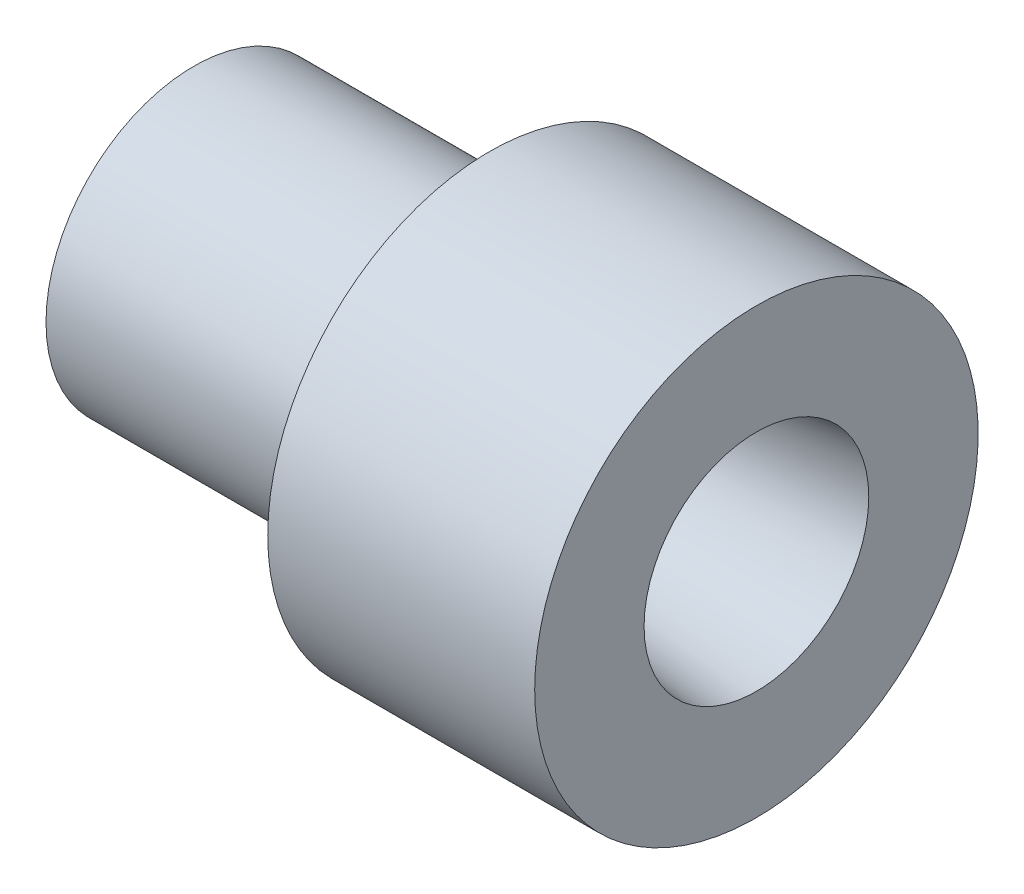
SolidWorks part; units mm, degrees
ref_plane "Front Plane" through (0, 0, 0) normal (0, 0, 1) x (1, 0, 0)
ref_plane "Top Plane" through (0, 0, 0) normal (0, 1, 0) x (1, 0, 0)
ref_plane "Right Plane" through (0, 0, 0) normal (1, 0, 0) x (0, 0, -1)
sketch "Sketch1" plane through (0, 0, 0) normal (0, 1, 0) x (1, 0, 0)
  line L0 (0, 0) -> (0, 2.286) construction
  line L1 (0, 2.286) -> (0, 6.35)
  line L2 (12.7, 9.525) -> (24.1665, 9.525)
  line L3 (24.1665, 9.525) -> (24.1665, 4.826)
  line L4 (24.1665, 4.826) -> (0, 2.286)
  line L5 (0, 0) -> (24.1665, 0) construction
  line L6 (24.1665, 0) -> (24.1665, 4.826) construction
  line L8 (12.7, 6.35) -> (12.7, 9.525)
  line L12 (0, 6.35) -> (12.7, 6.35)
  dimension "D1" = 2.286
  dimension "D2" = 4.826
  dimension "D3" = 6
  dimension "D4" = 9.525
  dimension "D5" = 6.35
  dimension "D6" = 12.7
revolve "Revolve1" add sketch "Sketch1" angle 360 about L5
equation "\"z\" = 8\t\t\t\t'number of blades"
equation "\"de\" = 0.43in\t\t\t'entrance eye diameter"
equation "\"de_length\" = 4mm\t\t'entrance eye consistent length"
equation "\"d_exit\" = 0.18in \t\t'throat aka d1"
equation "\"d2\" = 2.1in \t\t\t'outer diameter of the impeller"
equation "\"b2\" = .2in\t\t\t'tip height from disc surface at d2; slightly higher than d_exit"
equation "\"b1\" = \"b2\" + (\"d2\"/2 - \"de\"/2)*tan(\"theta\") \t\t\t'tip height from disc surface at inlet eye"
equation "\"theta\" = 12\t\t\t'angle of blades from inner to outer "
equation "\"ae\" = 3.14*(\"de\"^2)/4\t\t'entrance eye area'"
equation "\"ce\" = 3.14*\"de\"\t\t'entrance eye circumference"
equation "\"av_ratio\" = .325\t\t'ratio of av/ae at N_s of 470, range is .275 to .375, .325 ideal. High ratio means bigger area means smaller blades"
equation "\"av\" = \"ae\"*\"av_ratio\"\t\t'area between just two blades"
equation "\"s_open\" = \"av\"/\"b1\"\t\t'width of open area"
equation "\"s\"=\"ce\" - \"z\"*\"s_open\""
equation "\"min blade thickness\" = .15in"
equation "\"bearing OD\" = 30mm"
equation "\"bearing ID\"= 10mm"
equation "\"bearing depth\"= 9mm"
equation "\"bearing outer race thickness\"= 1mm"
equation "\"bearing inner race thickness\"= 1mm"
equation "\"bearing bore\" = \"bearing depth\" + 1mm"
equation "\"lower seal OD\" = .917in\t\t'this is https://www.mcmaster.com/#9281k121/=174001b"
equation "\"lower seal ID\"= .375in"
equation "\"lower seal depth\" = .625in + .218in"
equation "\"lower seal bore\" = \"lower seal depth\" + 1mm"
equation "\"upper seal OD\" = 1.125in\t'this is https://www.mcmaster.com/#5154t33/=173zuau, needs to be visually inspected before machining!"
equation "\"upper seal ID\"= 0.625in"
equation "\"upper seal depth\"= .25in\t'aka height; these values need to be confirmed by inspection!! We may want to compress the height."
equation "\"upper seal bore\" = \"upper seal depth\" + 1mm"
equation "\"big o-ring thickness\" = .139in"
equation "\"big o-ring OD\" = 2.734in"
equation "\"big o-ring ID\" = 3.012in"
equation "\"big o-ring groove depth\" = \"big o-ring thickness\"*4/5"
equation "\"impeller center height\" = \"impeller base thickness\" + \"b1\"\t'impeller height at de"
equation "\"impeller outer height\" = \"impeller base thickness\" + \"b2\"\t'impeller height at de"
equation "\"impeller upper clearance\"= .5mm"
equation "\"impeller horizontal clearance\"= (\"d2\"*1.15 - \"d2\")/2 \t\t'clearance based on D2-D3 ratio for circular volute, ranges 1.15 to 1.2"
equation "\"impeller bottom clearance\"= .5mm"
equation "\"impeller base thickness\"= 2mm"
equation "\"impeller dowel diameter\" = 2mm"
equation "\"impeller bolt head diameter\" = \"m4 head bore diameter\""
equation "\"impeller bolt head depth\" = 4mm"
equation "\"impeller bolt stop depth\" = 3mm"
equation "\"impeller bolt bore\" = \"m4 clearance\""
equation "\"impeller shaft bore depth\" = 12mm"
equation "\"impeller shaft bore\" = 8mm"
equation "\"impeller boss depth\" = \"impeller shaft bore depth\"+\"impeller bolt stop depth\"+\"impeller bolt head depth\"-\"impeller base thickness\""
equation "\"impeller boss diameter\" = \"upper seal ID\""
equation "\"impeller dowel length\" = 2mm*2 + \"impeller shaft bore\""
equation "\"coupler motor shaft hole ID\"= 8mm"
equation "\"coupler OD\"= 17mm"
equation "\"coupler length\"= 25mm"
equation "\"motor OD\" = 64mm"
equation "\"motor shaft diameter\"= 8mm"
equation "\"motor shaft pride\"= 32mm"
equation "\"motor to bearing plate distance\" = \"motor shaft pride\" + 2mm +\"coupler length\"/2"
equation "\"square plate bolt bore\" = \"m8 clearance\""
equation "\"square plate bolt head diameter\" = 13.5mm"
equation "\"square plate bolt head depth\" = 8mm"
equation "\"square plate bolt pattern diameter\"= 3.5in"
equation "\"motor mount center bore\"= \"coupler OD\"+ 4mm"
equation "\"motor mount post radius\"= ( 3 * \"square plate bolt bore\" ) / 2"
equation "\"motor mount m4 screw hole diameter\"= 4mm"
equation "\"motor mount m4 head diameter\"= 7.25mm"
equation "\"motor mount m4 head depth\"= 4mm"
equation "\"motor mount m4 pattern diamater\" = 30mm"
equation "\"motor mount plate thickness\"= 8mm + \"motor mount m4 head depth\""
equation "\"bearing plate stop ID\" = \"bearing OD\" - 4mm"
equation "\"bearing plate stop depth\" = 3mm"
equation "\"bearing plate thickness\" = \"bearing bore\" + \"bearing plate stop depth\" + \"shaft bearing stop length\""
equation "\"lower seal plate lip depth\" = 2mm"
equation "\"lower seal plate lip ID\" = \"lower seal OD\" - 3mm"
equation "\"lower seal plate thickness\" = \"lower seal plate lip depth\" + \"lower seal bore\""
equation "\"shaft coupler section diameter\" = 8mm"
equation "\"shaft coupler section length\" = \"motor to bearing plate distance\" - \"motor shaft pride\" - 2mm"
equation "\"shaft bearing section diameter\" = \"bearing ID\""
equation "\"shaft bearing section length\" = \"bearing plate stop depth\" + \"bearing depth\""
equation "\"shaft bearing stop diameter\" = \"bearing ID\" + 4mm"
equation "\"shaft bearing stop length\" = 3mm"
equation "\"shaft lower seal section diameter\" = \"lower seal ID\""
equation "\"shaft lower seal section length\" = \"lower seal plate thickness\" + 1mm"
equation "\"shaft impeller section diameter\" = \"impeller shaft bore\""
equation "\"shaft impeller section length\" = \"upper seal plate thickness\" + \"upper seal plate riser\" + \"impeller bottom clearance\" + \"impeller base thickness\" - \"impeller bolt head depth\" - \"impeller bolt stop depth\""
equation "\"upper seal plate thickness\" = \"upper seal plate pressure hole diameter\"+10mm"
equation "\"upper seal plate lip ID\" = \"upper seal OD\" - 3mm"
equation "\"upper seal plate riser\" = 6.59mm \t\t'this number needs to be read from the housing file"
equation "\"upper seal plate pressure hole diameter\" = .125in\t'this is 1/8 drill "
equation "\"upper seal plate pressure tap diameter\" = .328125in \t'this is 21/64 drill for a 1/8 ANPT tap"
equation "\"upper seal plate pressure tap grip\" = 5mm\t\t'this is the area around the tap so it doesn't crack"
equation "\"upper seal plate pressure tap depth\" = 12mm"
equation "\"impeller cavity center height\"= \"impeller bottom clearance\" + \"impeller upper clearance\" + \"impeller center height\""
equation "\"impeller cavity diameter\"= 2 * \"impeller horizontal clearance\" + \"d2\" \t\t\t\t\t\t\t\t\t'called D3 analytically"
equation "\"impeller cavity outer height\"= \"impeller bottom clearance\" + \"impeller upper clearance\" + \"impeller base thickness\" + \"b2\" \t\t'this is height at impeller diameter d2, not at d3"
equation "\"impeller housing thickness\"= \"impeller housing exit threaded diameter\" + 2*\"impeller housing outlet grip\""
equation "\"impeller housing diameter\" = \"square plate bolt pattern diameter\" + 2*\"motor mount post radius\""
equation "\"impeller housing bolt count\" = 8"
equation "\"impeller housing bolt diameter\" = \"m6 clearance\""
equation "\"impeller housing bolt pattern diameter\" = 3.5in"
equation "\"impeller housing threaded inlet diameter\" = 0.71875in \t'this is the 23/32 drill size for 1/2 NPT fitting https://www.mcmaster.com/#50715k269/=176pljy"
equation "\"impeller housing threaded inlet depth\"= .6in"
equation "\"impeller housing exit threaded diameter\"= 0.515625in \t\t'this is the 33/64 drill size for 9/16-18 fitting, expecting swagelok SS-8FK0-1-6STH fitting"
equation "\"impeller housing exit threaded depth\"= 10mm"
equation "\"impeller housing diffuser conical angle\"=10"
equation "\"impeller housing diffuser tangent angle\"=5"
equation "\"impeller housing diffuser final diameter\" = .38in\t\t'aka d2'"
equation "\"impeller housing outlet grip\" = 5mm"
equation "\"end mill size\" = 0.375in\t'for 3/8 endmill"
equation "\"m4 clearance\" = 0.171875in \t'this is 11/64 bit for 4.36mm"
equation "\"m4 tap\" = 0.125in\t\t'this is 1/8 bit for 3.17mm"
equation "\"m4 head bore diameter\" = 7.5mm"
equation "\"m4 head bore depth\" = 5mm\t'actual is ~4mm"
equation "\"m6 clearance\" = 0.234375in\t'this is 15/64 bit = 5.95mm, could use 6mm bit, B bit for 6.04mm or 1/4 bit for 6.35mm"
equation "\"m6 tap\" = 5mm\t\t\t'5mm is appropriate, could use 13/64 or #5,6,7"
equation "\"m6 head bore diameter\" = 11mm\t\t"
equation "\"m6 head bore depth\" = 7mm\t'actual is 6mm"
equation "\"m8 clearance\" = 0.3125in\t'this is 5/16in for 7.93mm, could use 8mm, O,P, or 21/64"
equation "\"m8 tap\" = 0.265625in\t\t'this is 17/64 for 6.746875mm"
equation "\"m8 head bore diameter\" = 14mm"
equation "\"m8 head bore depth\" = 9mm\t'actual is 8mm"
equation "\"D1@Sketch1\"=\"d_exit\"/2"
equation "\"D2@Sketch1\"=\"impeller housing diffuser final diameter\"/2"
equation "\"diffuser cartridge OD\" =.75in"
equation "\"D4@Sketch1\"=\"diffuser cartridge OD\"/2"
